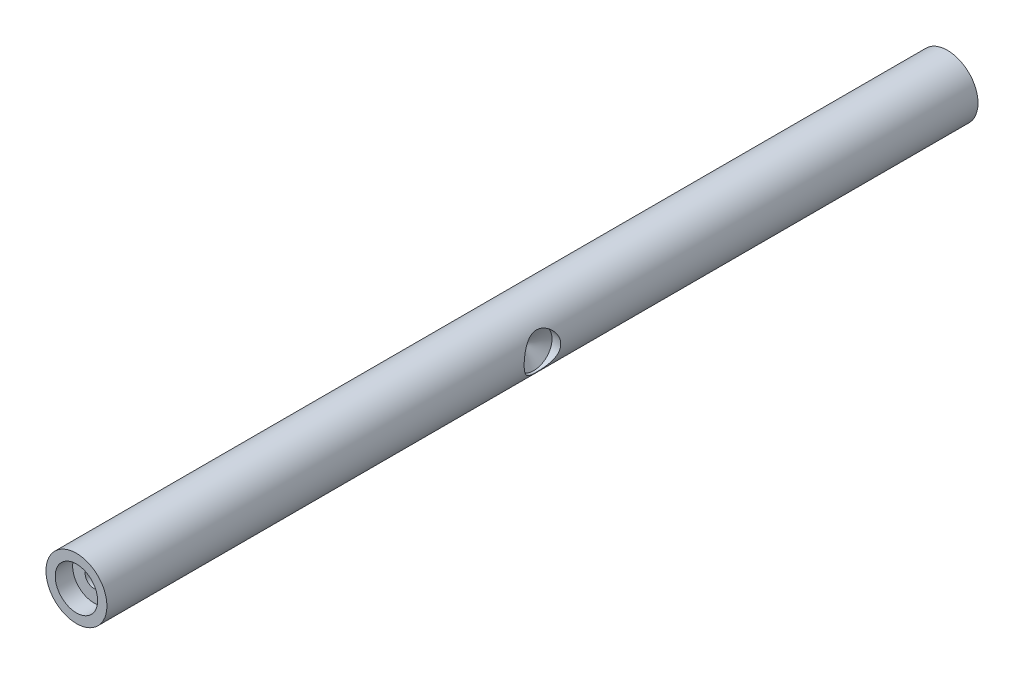
SolidWorks part; units mm, degrees
ref_plane "Piano frontale" through (0, 0, 0) normal (0, 0, 1) x (1, 0, 0)
ref_plane "Piano superiore" through (0, 0, 0) normal (0, 1, 0) x (1, 0, 0)
ref_plane "Piano destro" through (0, 0, 0) normal (1, 0, 0) x (0, 0, -1)
sketch "Schizzo1" plane through (0, 0, 0) normal (0, 0, 1) x (1, 0, 0)
  circle A0 centre (0, 0) radius 7
  dimension "D1" = 14
extrude "Estrusione-Estrusione1" add sketch "Schizzo1" along normal mid plane 200
sketch "Schizzo2" plane through (0, 0, 100) normal (0, 0, 1) x (1, 0, 0)
  circle A0 centre (0, 0) radius 2
  dimension "D1" = 4
extrude "Taglio-Estrusione1" cut sketch "Schizzo2" against normal up to next
sketch "Schizzo5" plane through (0, 0, 100) normal (0, 0, 1) x (1, 0, 0)
  circle A0 centre (0, 0) radius 4.87
extrude "Taglio-Estrusione2" cut sketch "Schizzo5" against normal blind 4
ref_plane "Piano1" through (7, 0, 0) normal (1, 0, 0) x (0, 0, -1)
hole_wizard "Foro per Vite M8-1" positions "Schizzo8" profile "Schizzo9" hole size "M8" standard "ISO"
sketch "Schizzo8" plane through (7, 0, 0) normal (1, 0, 0) x (0, 0, -1)
  point P0 (0, 0)
sketch "Schizzo9" plane through (7, 0, 0) normal (0, 1, 0) x (0, 0, -1)
  line L0 (0, 0) -> (0, 4.5236)
  line L1 (0, 4.5236) -> (4.2, 2)
  line L2 (4.2, 2) -> (4.2, 0)
  line L5 (4.2, 0) -> (0, 0)
  line L10 (0, 4.5236) -> (-4.2, 2) construction
  line L11 (0, -6.35) -> (0, 107.95) construction
  dimension "Hole Dia." = 8.4
  dimension "Hole Depth" = 2
  dimension "Drill Angle" = 118
